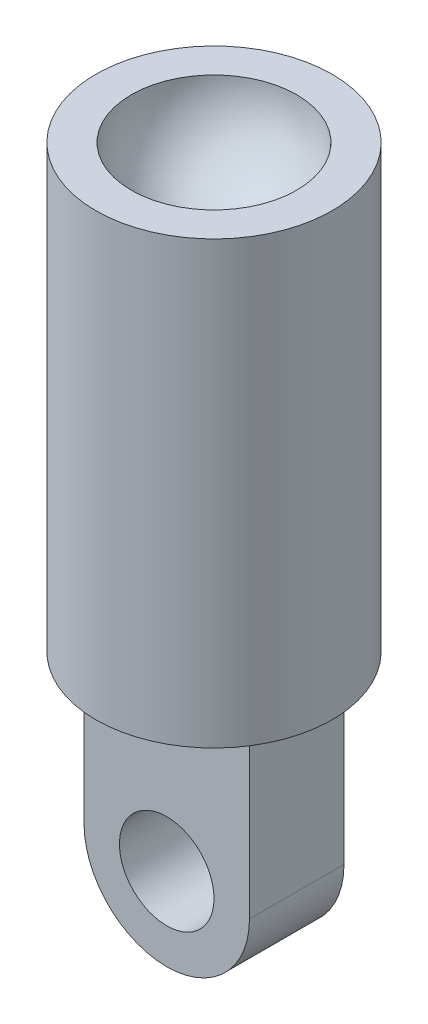
SolidWorks part; units mm, degrees
ref_plane "Ön Düzlem" through (0, 0, 0) normal (0, 0, 1) x (1, 0, 0)
ref_plane "Üst Düzlem" through (0, 0, 0) normal (0, 1, 0) x (1, 0, 0)
ref_plane "Sağ Düzlem" through (0, 0, 0) normal (1, 0, 0) x (0, 0, -1)
sketch "Sketch1" plane through (0, 0, 0) normal (0, 0, 1) x (1, 0, 0)
  line L4 (-7, 0) -> (-10, 0)
  line L5 (-10, 0) -> (-10, -37.3039)
  line L7 (7, 0) -> (10, 0)
  line L8 (10, 0) -> (10, -37.3039)
  line L14 (-10, -37.3039) -> (10, -37.3039)
  line L15 (0, 4.0247) -> (0, -52.9888) construction
  arc A0 (-7, 0) -> (7, 0) centre (0, 0) ccw
  dimension "D1" = 14
  dimension "D5" = 3
  dimension "D6" = 3
revolve "Revolve1" add sketch "Sketch1" angle 360 about L15
sketch "Sketch2" plane through (0, 0, 0) normal (0, 0, 1) x (1, 0, 0)
  line L1 (-10, -37.3039) -> (10, -37.3039) construction
  line L2 (-7, -51.4) -> (-7, -37.3039)
  line L3 (7, -51.4) -> (7, -37.3039)
  line L4 (10, 0) -> (-10, 0) construction
  line L6 (-7, -37.3039) -> (7, -37.3039)
  arc A0 (-7, -51.4) -> (7, -51.4) centre (0, -51.4) ccw
  circle A1 centre (0, -51.4) radius 4
  dimension "D1" = 14
  dimension "D3" = 8
  dimension "D2" = 51.4
extrude "Boss-Extrude1" add sketch "Sketch2" along normal mid plane 8
fillet "Fillet1" radius 1 4 edges at (0, -37.3039, -4) (7, -37.3039, 0) (0, -37.3039, 4) (-7, -37.3039, 0)
